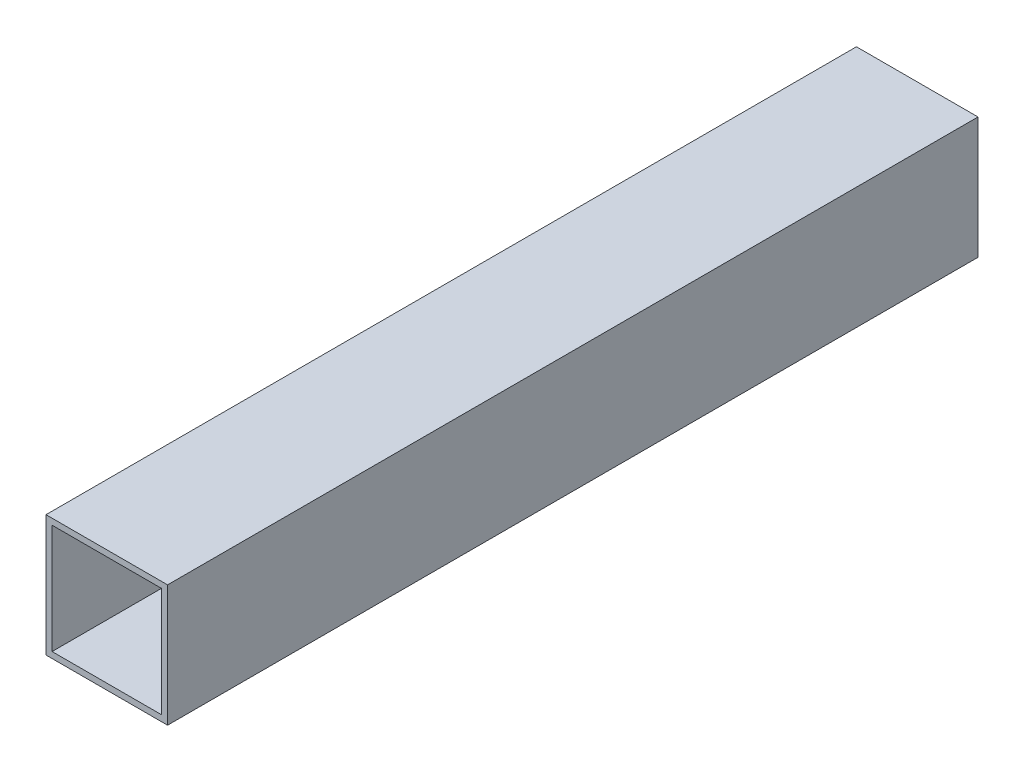
SolidWorks part; units mm, degrees
ref_plane "Front Plane" through (0, 0, 0) normal (0, 0, 1) x (1, 0, 0)
ref_plane "Top Plane" through (0, 0, 0) normal (0, 1, 0) x (1, 0, 0)
ref_plane "Right Plane" through (0, 0, 0) normal (1, 0, 0) x (0, 0, -1)
sketch "Sketch1" plane through (0, 0, 0) normal (0, 0, 1) x (1, 0, 0)
  line L1 (0, 0) -> (30, 0)
  line L2 (0, 0) -> (0, 30)
  line L3 (0, 30) -> (30, 30)
  line L4 (30, 0) -> (30, 30)
  line L5 (1.5, 1.5) -> (28.5, 1.5)
  line L6 (1.5, 1.5) -> (1.5, 28.5)
  line L7 (1.5, 28.5) -> (28.5, 28.5)
  line L8 (28.5, 1.5) -> (28.5, 28.5)
  dimension "D1" = 30
  dimension "D2" = 30
  dimension "D3" = 1.5
  dimension "D4" = 1.5
  dimension "D5" = 1.5
  dimension "D6" = 1.5
extrude "Boss-Extrude1" add sketch "Sketch1" along normal blind 200
